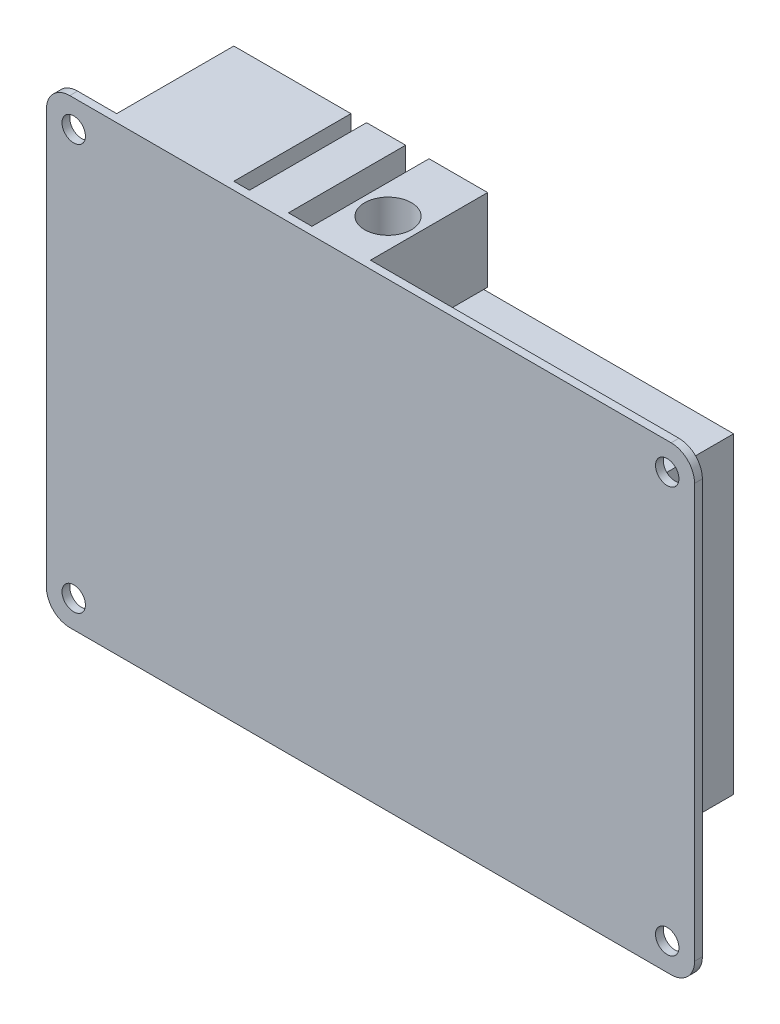
SolidWorks part; units mm, degrees
material "Custom Plastic"
ref_plane "Front Plane" through (0, 0, 0) normal (0, 0, 1) x (1, 0, 0)
ref_plane "Top Plane" through (0, 0, 0) normal (0, 1, 0) x (1, 0, 0)
ref_plane "Right Plane" through (0, 0, 0) normal (1, 0, 0) x (0, 0, -1)
sketch "Sketch1" plane through (0, 0, 0) normal (0, 0, 1) x (1, 0, 0)
  line L0 (-34.7741, 10.1603) -> (-31.2741, 10.1603)
  line L1 (-34.7741, 10.1603) -> (48.2259, 10.1603)
  line L2 (-34.7741, 10.1603) -> (-34.7741, -48.8397)
  line L3 (-34.7741, -48.8397) -> (48.2259, -48.8397)
  line L4 (48.2259, 10.1603) -> (48.2259, -48.8397)
  line L5 (-34.7741, 10.1603) -> (-34.7741, 6.205)
  line L6 (-31.2741, 10.1603) -> (-31.2741, 6.6603)
  line L7 (6.7259, 10.1603) -> (6.7259, -48.8397) construction
  line L8 (-34.7741, -19.3397) -> (48.2259, -19.3397) construction
  circle A0 centre (-31.2741, 6.6603) radius 1.5
  circle A1 centre (44.7259, 6.6603) radius 1.5
  circle A2 centre (44.7259, -45.3397) radius 1.5
  circle A3 centre (-31.2741, -45.3397) radius 1.5
  dimension "D5" = 3
  dimension "D1" = 83
  dimension "D2" = 59
  dimension "D3" = 3.5
  dimension "D4" = 3.5
extrude "Boss-Extrude1" add sketch "Sketch1" along normal blind 1
sketch "Sketch2" plane through (0, 0, 0) normal (0, 0, -1) x (-1, 0, 0)
  line L3 (34.7741, 10.1603) -> (-48.2259, 10.1603) construction
  line L4 (26.7741, -10.8397) -> (11.7741, -10.8397)
  line L5 (26.7741, -10.8397) -> (26.7741, 10.1603)
  line L6 (26.7741, 10.1603) -> (11.7741, 10.1603)
  line L7 (11.7741, -10.8397) -> (11.7741, 10.1603)
  line L9 (34.7741, -48.8397) -> (-48.2259, -48.8397) construction
  line L10 (26.7741, -31.8397) -> (13.7741, -31.8397)
  line L11 (26.7741, -31.8397) -> (26.7741, -48.8397)
  line L12 (26.7741, -48.8397) -> (13.7741, -48.8397)
  line L13 (13.7741, -31.8397) -> (13.7741, -48.8397)
  line L15 (9.7741, 10.1603) -> (4.7741, 10.1603)
  line L16 (9.7741, 10.1603) -> (9.7741, -8.8397)
  line L17 (9.7741, -8.8397) -> (4.7741, -8.8397)
  line L18 (4.7741, 10.1603) -> (4.7741, -8.8397)
  line L19 (1.7741, 10.1603) -> (-5.7259, 10.1603)
  line L20 (2.7741, -0.8397) -> (-37.2259, -0.8397)
  line L21 (2.7741, -0.8397) -> (2.7741, -40.8397)
  line L22 (2.7741, -40.8397) -> (-37.2259, -40.8397)
  line L23 (-37.2259, -0.8397) -> (-37.2259, -40.8397)
  line L24 (1.7741, 10.1603) -> (1.7741, -0.3397)
  line L25 (1.7741, -0.3397) -> (-5.7259, -0.3397)
  line L26 (-5.7259, 10.1603) -> (-5.7259, -0.3397)
extrude "Boss-Extrude2" add sketch "Sketch2" along normal blind 15
sketch "Sketch3" plane through (0, 10.1603, 0) normal (0, 1, 0) x (1, 0, 0)
  circle A0 centre (1.9759, 6) radius 3
extrude "Cut-Extrude1" cut sketch "Sketch3" against normal blind 5
sketch "Sketch4" plane through (0, -48.8397, 0) normal (0, -1, 0) x (1, 0, 0)
  line L7 (-14.7741, -7) -> (-25.7741, -7)
  line L16 (-14.7741, -7) -> (-14.7741, -2)
  line L17 (-14.7741, -2) -> (-25.7741, -2)
  line L18 (-25.7741, -7) -> (-25.7741, -2)
  line L20 (-14.7741, -14) -> (-25.7741, -14)
  line L21 (-14.7741, -14) -> (-14.7741, -9)
  line L22 (-14.7741, -9) -> (-25.7741, -9)
  line L23 (-25.7741, -14) -> (-25.7741, -9)
  dimension "D1" = 11
  dimension "D2" = 5
extrude "Cut-Extrude2" cut sketch "Sketch4" against normal blind 10
fillet "Fillet1" radius 3 4 edges at (48.2259, 10.1603, 0.5) (48.2259, -48.8397, 0.5) (-34.7741, 10.1603, 0.5) (-34.7741, -48.8397, 0.5)
ref_plane "Plane1" through (6.7259, 0, 0) normal (-1, 0, 0) x (0, 0, 1)
ref_plane "Plane2" through (0, -19.3397, 0) normal (0, 1, 0) x (1, 0, 0)
